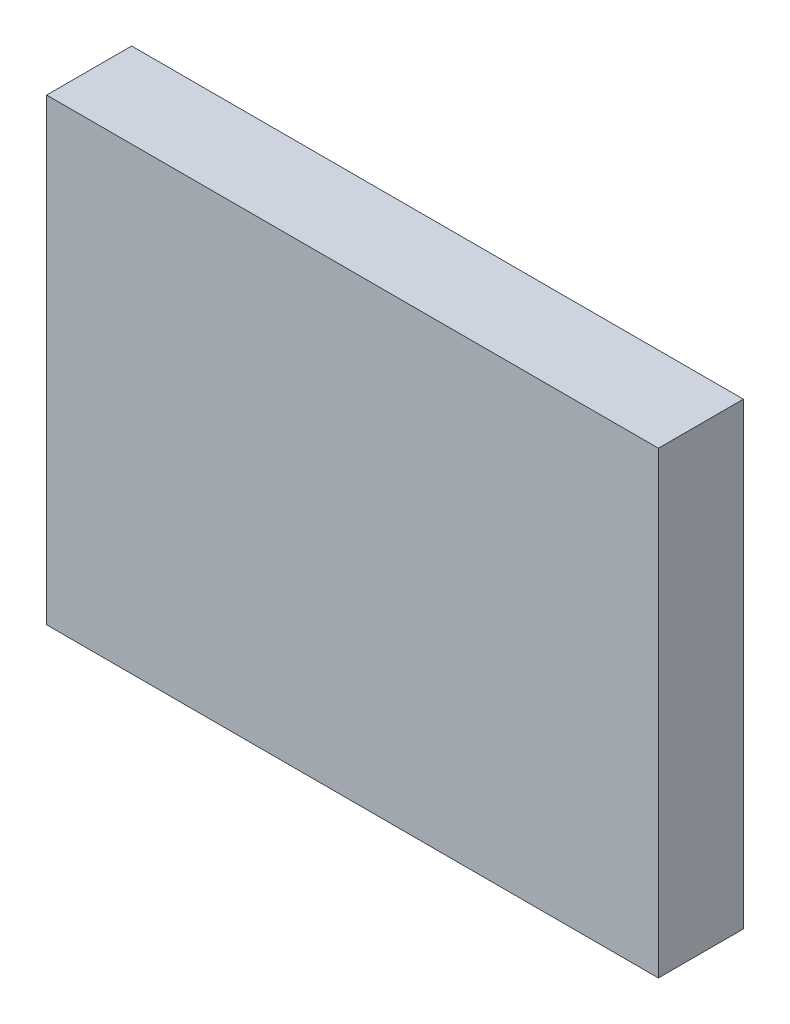
SolidWorks part; units mm, degrees
ref_plane "Спереди" through (0, 0, 0) normal (0, 0, 1) x (1, 0, 0)
ref_plane "Сверху" through (0, 0, 0) normal (0, 1, 0) x (1, 0, 0)
ref_plane "Справа" through (0, 0, 0) normal (1, 0, 0) x (0, 0, -1)
sketch "Эскиз1" plane through (0, 0, 0) normal (0, 0, 1) x (1, 0, 0)
  line L1 (-180, 135) -> (180, 135)
  line L2 (-180, 135) -> (-180, -135)
  line L3 (-180, -135) -> (180, -135)
  line L4 (180, 135) -> (180, -135)
  line L5 (-180, 135) -> (180, -135) construction
  line L6 (-180, -135) -> (180, 135) construction
  point P0 (0, 0)
extrude "Бобышка-Вытянуть1" add sketch "Эскиз1" along normal blind 50
sketch "шлифовка" plane through (0, 0, 50) normal (0, 0, 1) x (1, 0, 0)
  line L1 (-34.1581, 21.8035) -> (-171.6039, 21.8035)
  line L2 (-34.1581, 21.8035) -> (-34.1581, 9.8035)
  line L3 (-34.1581, 9.8035) -> (-171.6039, 9.8035)
  line L4 (-171.6039, 21.8035) -> (-171.6039, 9.8035)
sketch3d "Трехмерный эскиз1"
  point P0 (0, 0, 50.02)
sketch "Перлаж" plane through (0, 0, 50) normal (0, 0, 1) x (1, 0, 0)
  circle A149 centre (-138.9139, -222.6641) radius 1.47
  circle A150 centre (-137.3639, -222.6641) radius 1.47
  circle A151 centre (-135.8139, -222.6641) radius 1.47
  circle A152 centre (-134.2639, -222.6641) radius 1.47
  circle A153 centre (-132.7139, -222.6641) radius 1.47
  circle A154 centre (-131.1639, -222.6641) radius 1.47
  circle A155 centre (-129.6139, -222.6641) radius 1.47
  circle A156 centre (-128.0639, -222.6641) radius 1.47
  circle A157 centre (-126.5139, -222.6641) radius 1.47
  circle A158 centre (-124.9639, -222.6641) radius 1.47
  circle A159 centre (-137.3639, -221.1141) radius 1.47
  circle A160 centre (-135.8139, -221.1141) radius 1.47
  circle A161 centre (-134.2639, -221.1141) radius 1.47
  circle A162 centre (-132.7139, -221.1141) radius 1.47
  circle A163 centre (-131.1639, -221.1141) radius 1.47
  circle A164 centre (-129.6139, -221.1141) radius 1.47
  circle A165 centre (-128.0639, -221.1141) radius 1.47
  circle A166 centre (-126.5139, -221.1141) radius 1.47
  circle A167 centre (-124.9639, -221.1141) radius 1.47
  circle A168 centre (-137.3639, -219.5641) radius 1.47
  circle A169 centre (-135.8139, -219.5641) radius 1.47
  circle A170 centre (-134.2639, -219.5641) radius 1.47
  circle A171 centre (-132.7139, -219.5641) radius 1.47
  circle A172 centre (-131.1639, -219.5641) radius 1.47
  circle A173 centre (-129.6139, -219.5641) radius 1.47
  circle A174 centre (-128.0639, -219.5641) radius 1.47
  circle A175 centre (-126.5139, -219.5641) radius 1.47
  circle A176 centre (-124.9639, -219.5641) radius 1.47
  circle A177 centre (-137.3639, -218.0141) radius 1.47
  circle A178 centre (-135.8139, -218.0141) radius 1.47
  circle A179 centre (-134.2639, -218.0141) radius 1.47
  circle A180 centre (-132.7139, -218.0141) radius 1.47
  circle A181 centre (-131.1639, -218.0141) radius 1.47
  circle A182 centre (-129.6139, -218.0141) radius 1.47
  circle A183 centre (-128.0639, -218.0141) radius 1.47
  circle A184 centre (-126.5139, -218.0141) radius 1.47
  circle A185 centre (-124.9639, -218.0141) radius 1.47
  circle A186 centre (-137.3639, -216.4641) radius 1.47
  circle A187 centre (-135.8139, -216.4641) radius 1.47
  circle A188 centre (-134.2639, -216.4641) radius 1.47
  circle A189 centre (-132.7139, -216.4641) radius 1.47
  circle A190 centre (-131.1639, -216.4641) radius 1.47
  circle A191 centre (-129.6139, -216.4641) radius 1.47
  circle A192 centre (-128.0639, -216.4641) radius 1.47
  circle A193 centre (-126.5139, -216.4641) radius 1.47
  circle A194 centre (-124.9639, -216.4641) radius 1.47
  circle A195 centre (-137.3639, -214.9141) radius 1.47
  circle A196 centre (-135.8139, -214.9141) radius 1.47
  circle A197 centre (-134.2639, -214.9141) radius 1.47
  circle A198 centre (-132.7139, -214.9141) radius 1.47
  circle A199 centre (-131.1639, -214.9141) radius 1.47
  circle A200 centre (-129.6139, -214.9141) radius 1.47
  circle A201 centre (-128.0639, -214.9141) radius 1.47
  circle A202 centre (-126.5139, -214.9141) radius 1.47
  circle A203 centre (-124.9639, -214.9141) radius 1.47
  circle A204 centre (-137.3639, -213.3641) radius 1.47
  circle A205 centre (-135.8139, -213.3641) radius 1.47
  circle A206 centre (-134.2639, -213.3641) radius 1.47
  circle A207 centre (-132.7139, -213.3641) radius 1.47
  circle A208 centre (-131.1639, -213.3641) radius 1.47
  circle A209 centre (-129.6139, -213.3641) radius 1.47
  circle A210 centre (-128.0639, -213.3641) radius 1.47
  circle A211 centre (-126.5139, -213.3641) radius 1.47
  circle A212 centre (-124.9639, -213.3641) radius 1.47
  circle A213 centre (-137.3639, -211.8141) radius 1.47
  circle A214 centre (-135.8139, -211.8141) radius 1.47
  circle A215 centre (-134.2639, -211.8141) radius 1.47
  circle A216 centre (-132.7139, -211.8141) radius 1.47
  circle A217 centre (-131.1639, -211.8141) radius 1.47
  circle A218 centre (-129.6139, -211.8141) radius 1.47
  circle A219 centre (-128.0639, -211.8141) radius 1.47
  circle A220 centre (-126.5139, -211.8141) radius 1.47
  circle A221 centre (-124.9639, -211.8141) radius 1.47
  circle A222 centre (-137.3639, -210.2641) radius 1.47
  circle A223 centre (-135.8139, -210.2641) radius 1.47
  circle A224 centre (-134.2639, -210.2641) radius 1.47
  circle A225 centre (-132.7139, -210.2641) radius 1.47
  circle A226 centre (-131.1639, -210.2641) radius 1.47
  circle A227 centre (-129.6139, -210.2641) radius 1.47
  circle A228 centre (-128.0639, -210.2641) radius 1.47
  circle A229 centre (-126.5139, -210.2641) radius 1.47
  circle A230 centre (-124.9639, -210.2641) radius 1.47
  circle A231 centre (-137.3639, -208.7141) radius 1.47
  circle A232 centre (-135.8139, -208.7141) radius 1.47
  circle A233 centre (-134.2639, -208.7141) radius 1.47
  circle A234 centre (-132.7139, -208.7141) radius 1.47
  circle A235 centre (-131.1639, -208.7141) radius 1.47
  circle A236 centre (-129.6139, -208.7141) radius 1.47
  circle A237 centre (-128.0639, -208.7141) radius 1.47
  circle A238 centre (-126.5139, -208.7141) radius 1.47
  circle A239 centre (-124.9639, -208.7141) radius 1.47
  circle A240 centre (-138.9139, -221.1141) radius 1.47
  circle A241 centre (-138.9139, -219.5641) radius 1.47
  circle A242 centre (-138.9139, -218.0141) radius 1.47
  circle A243 centre (-138.9139, -216.4641) radius 1.47
  circle A244 centre (-138.9139, -214.9141) radius 1.47
  circle A245 centre (-138.9139, -213.3641) radius 1.47
  circle A246 centre (-138.9139, -211.8141) radius 1.47
  circle A247 centre (-138.9139, -210.2641) radius 1.47
  circle A248 centre (-138.9139, -208.7141) radius 1.47
  dimension "D1" = 10
  dimension "D2" = 10
